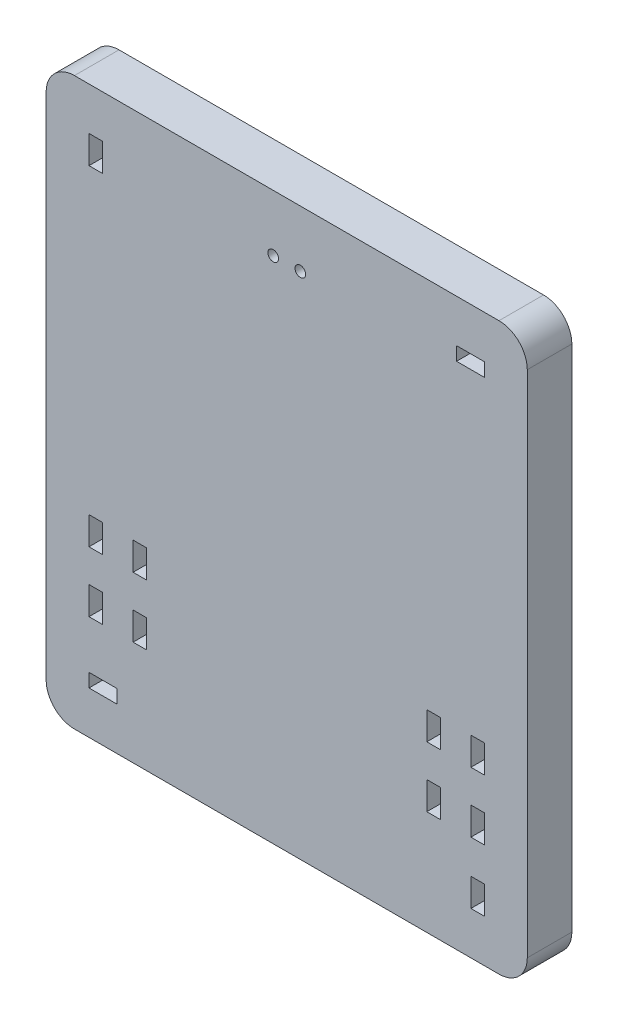
SolidWorks part; units mm, degrees
ref_plane "Front" through (0, 0, 0) normal (0, 0, 1) x (1, 0, 0)
ref_plane "Top" through (0, 0, 0) normal (0, 1, 0) x (1, 0, 0)
ref_plane "Right" through (0, 0, 0) normal (1, 0, 0) x (0, 0, -1)
sketch "Sketch1" plane through (0, 0, 0) normal (0, 0, 1) x (1, 0, 0)
  line L0 (-0.0214, 120.65) -> (-0.0214, 6.35)
  line L1 (6.3286, 0) -> (101.6, 0)
  line L2 (107.95, 6.35) -> (107.95, 120.65)
  line L3 (15.8536, 12.6539) -> (15.8536, 9.6139)
  line L4 (53.9643, 127) -> (53.9643, 0) construction
  line L5 (6.3286, 127) -> (101.6, 127)
  line L6 (-0.0214, 63.5) -> (107.95, 63.5) construction
  line L7 (9.5925, 12.6539) -> (15.8536, 12.6539)
  line L8 (9.5925, 9.6139) -> (15.8536, 9.6139)
  line L9 (9.5925, 12.6539) -> (9.5925, 9.6139)
  line L10 (92.075, 114.3461) -> (92.075, 117.3861)
  line L11 (98.3361, 114.3461) -> (92.075, 114.3461)
  line L12 (98.3361, 117.3861) -> (92.075, 117.3861)
  line L13 (98.3361, 114.3461) -> (98.3361, 117.3861)
  line L14 (9.5925, 111.125) -> (9.5925, 117.3861)
  line L15 (9.5925, 117.3861) -> (12.6325, 117.3861)
  line L16 (9.5925, 111.125) -> (12.6325, 111.125)
  line L17 (12.6325, 111.125) -> (12.6325, 117.3861)
  line L18 (9.5925, 23.4684) -> (12.6325, 23.4684)
  line L19 (9.5925, 23.4684) -> (9.5925, 29.7225)
  line L20 (9.5925, 29.7225) -> (12.6325, 29.7225)
  line L21 (12.6325, 29.7225) -> (12.6325, 23.4684)
  line L22 (95.2961, 29.7225) -> (95.2961, 23.4684)
  line L23 (98.3361, 29.7225) -> (95.2961, 29.7225)
  line L24 (98.3361, 23.4684) -> (98.3361, 29.7225)
  line L25 (98.3361, 23.4684) -> (95.2961, 23.4684)
  line L26 (9.5925, 37.0503) -> (12.6325, 37.0503)
  line L27 (12.6325, 37.0503) -> (12.6325, 43.3044)
  line L28 (12.6325, 43.3044) -> (9.5925, 43.3044)
  line L29 (9.5925, 43.3044) -> (9.5925, 37.0503)
  line L30 (98.3361, 15.875) -> (98.3361, 9.6139)
  line L31 (98.3361, 9.6139) -> (95.2961, 9.6139)
  line L32 (98.3361, 43.3044) -> (98.3361, 37.0503)
  line L33 (95.2961, 43.3044) -> (98.3361, 43.3044)
  line L34 (95.2961, 37.0503) -> (95.2961, 43.3044)
  line L35 (98.3361, 37.0503) -> (95.2961, 37.0503)
  line L36 (98.3361, 15.875) -> (95.2961, 15.875)
  line L37 (95.2961, 15.875) -> (95.2961, 9.6139)
  line L38 (19.4905, 29.7225) -> (19.4905, 23.4684)
  line L39 (19.4905, 23.4684) -> (22.5305, 23.4684)
  line L40 (19.4905, 29.7225) -> (22.5305, 29.7225)
  line L41 (22.5305, 29.7225) -> (22.5305, 23.4684)
  line L42 (19.4905, 37.0503) -> (22.5305, 37.0503)
  line L43 (22.5305, 37.0503) -> (22.5305, 43.3044)
  line L44 (22.5305, 43.3044) -> (19.4905, 43.3044)
  line L45 (19.4905, 43.3044) -> (19.4905, 37.0503)
  line L46 (85.3981, 29.7225) -> (85.3981, 23.4684)
  line L47 (88.4381, 29.7225) -> (85.3981, 29.7225)
  line L48 (88.4381, 23.4684) -> (85.3981, 23.4684)
  line L49 (88.4381, 29.7225) -> (88.4381, 23.4684)
  line L50 (88.4381, 43.3044) -> (88.4381, 37.0503)
  line L51 (85.3981, 43.3044) -> (88.4381, 43.3044)
  line L52 (88.4381, 37.0503) -> (85.3981, 37.0503)
  line L53 (85.3981, 37.0503) -> (85.3981, 43.3044)
  arc A0 (-0.0214, 6.35) -> (6.3286, 0) centre (6.3286, 6.35) ccw
  arc A1 (107.95, 6.35) -> (101.6, 0) centre (101.6, 6.35) cw
  arc A2 (6.3286, 127) -> (-0.0214, 120.65) centre (6.3286, 120.65) ccw
  arc A3 (107.95, 120.65) -> (101.6, 127) centre (101.6, 120.65) ccw
  circle A4 centre (50.927, 114.3) radius 1.1938
  circle A5 centre (57.023, 114.3) radius 1.1938
  dimension "D1" = 6.35
  dimension "D3" = 6.35
  dimension "D4" = 6.35
  dimension "D5" = 114.3
  dimension "D6" = 95.2714
  dimension "D2" = 6.35
  dimension "D9" = 2.3876
  dimension "D10" = 3.0373
  dimension "D11" = 12.7
  dimension "D12" = 6.096
  dimension "D13" = 2.3876
  dimension "D14" = 12.7
  dimension "D15" = 3.0587
  dimension "D7" = 6.3286
  dimension "D8" = 6.35
  dimension "D16" = 9.6139
  dimension "D17" = 9.6139
  dimension "D18" = 9.6139
  dimension "D19" = 3.04
  dimension "D20" = 9.6139
  dimension "D21" = 3.04
  dimension "D22" = 6.2541
  dimension "D23" = 23.4684
  dimension "D24" = 3.04
  dimension "D25" = 6.2541
  dimension "D26" = 7.3278
  dimension "D27" = 9.6139
  dimension "D28" = 6.858
  dimension "D29" = 3.04
  dimension "D30" = 6.2541
  dimension "D31" = 23.4684
  dimension "D32" = 6.2541
  dimension "D33" = 3.04
  dimension "D34" = 19.5119
  dimension "D35" = 9.6139
  dimension "D36" = 6.2611
  dimension "D37" = 3.04
  dimension "D38" = 6.2611
  dimension "D39" = 3.04
  dimension "D40" = 6.2611
  dimension "D41" = 6.2611
  dimension "D42" = 3.04
  dimension "D43" = 9.6139
  dimension "D44" = 9.6139
  dimension "D45" = 6.2611
  dimension "D46" = 3.04
  dimension "D47" = 9.6139
  dimension "D48" = 9.6139
  dimension "D49" = 6.2611
  dimension "D50" = 3.04
  dimension "D51" = 6.2611
  dimension "D52" = 3.04
extrude "Boss-Extrude1" add sketch "Sketch1" along normal blind 10
